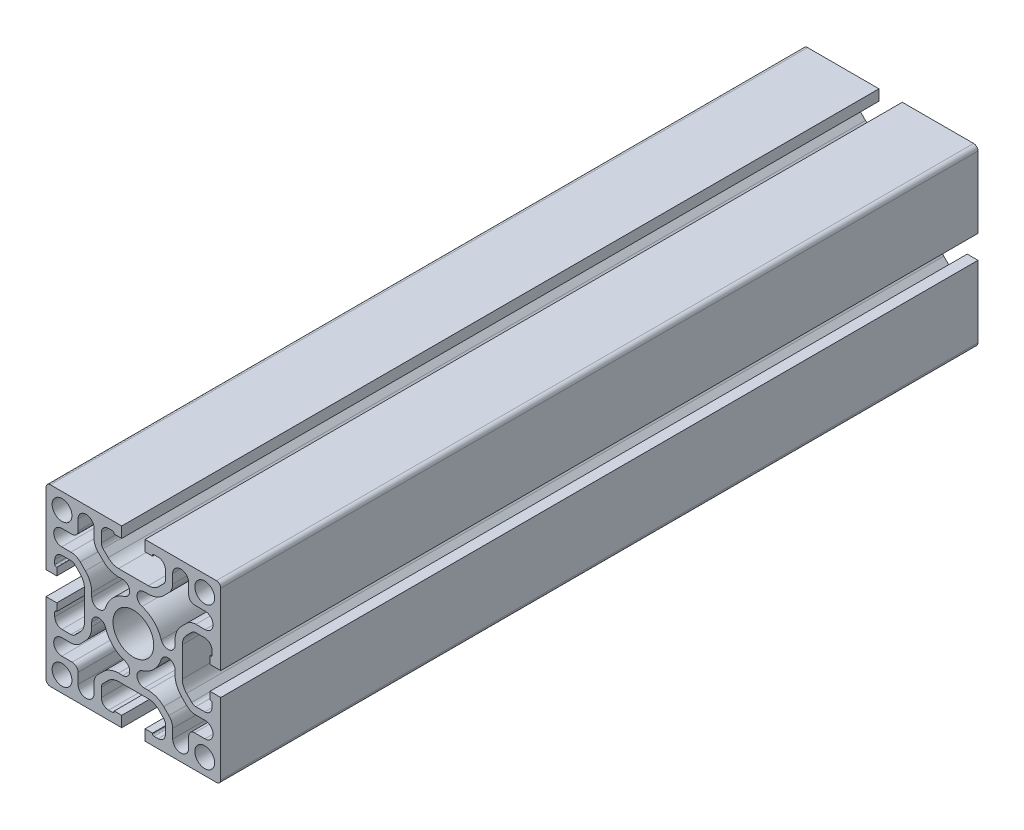
SolidWorks part; units mm, degrees
ref_plane "Płaszczyzna przednia" through (0, 0, 0) normal (0, 0, 1) x (1, 0, 0)
ref_plane "Płaszczyzna górna" through (0, 0, 0) normal (0, 1, 0) x (1, 0, 0)
ref_plane "Płaszczyzna prawa" through (0, 0, 0) normal (1, 0, 0) x (0, 0, -1)
ref_plane "Plane1" through (0, 0, 0) normal (0, 0, -1) x (-1, 0, 0)
sketch "Sketch1" plane through (0, 0, 0) normal (0, 0, -1) x (-1, 0, 0)
  line L0 (5.1034, -14.3) -> (3.6784, -14.3)
  line L1 (14.3, -3.6784) -> (14.3, -5.1134)
  line L2 (16.4818, -10.4017) -> (18.2431, -12.173)
  line L3 (21.434, -13.5) -> (24.6, -13.5)
  line L4 (24.6, -19) -> (21, -19)
  line L5 (19, -21) -> (19, -24.6)
  line L6 (13.5, -24.6) -> (13.5, -21.454)
  line L7 (12.182, -18.272) -> (10.4067, -16.4967)
  line L8 (-3.6784, -14.3) -> (-5.1034, -14.3)
  line L9 (-10.4067, -16.4967) -> (-12.182, -18.272)
  line L10 (-13.5, -21.454) -> (-13.5, -24.6)
  line L11 (-19, -24.6) -> (-19, -21)
  line L12 (-21, -19) -> (-24.6, -19)
  line L13 (-24.6, -13.5) -> (-21.434, -13.5)
  line L14 (-18.2431, -12.173) -> (-16.4818, -10.4017)
  line L15 (-14.3, -5.1134) -> (-14.3, -3.6784)
  line L16 (-5.1034, 14.3) -> (-3.6784, 14.3)
  line L17 (-14.3, 3.6784) -> (-14.3, 5.1134)
  line L18 (-16.4818, 10.4017) -> (-18.2431, 12.173)
  line L19 (-21.434, 13.5) -> (-24.6, 13.5)
  line L20 (-24.6, 19) -> (-21, 19)
  line L21 (-19, 21) -> (-19, 24.6)
  line L22 (-13.5, 24.6) -> (-13.5, 21.454)
  line L23 (-12.182, 18.272) -> (-10.4067, 16.4967)
  line L24 (3.6784, 14.3) -> (5.1034, 14.3)
  line L25 (10.4067, 16.4967) -> (12.182, 18.272)
  line L26 (13.5, 21.454) -> (13.5, 24.6)
  line L27 (19, 24.6) -> (19, 21)
  line L28 (21, 19) -> (24.6, 19)
  line L29 (24.6, 13.5) -> (21.434, 13.5)
  line L30 (18.2431, 12.173) -> (16.4818, 10.4017)
  line L31 (14.3, 5.1134) -> (14.3, 3.6784)
  line L32 (5.1, 16.8) -> (-5.11, 16.8)
  line L33 (-8.6455, 18.2645) -> (-10.42, 20.04)
  line L34 (-11, 21.45) -> (-11, 24.5)
  line L35 (-8.5, 27) -> (-7.07, 27)
  line L36 (-6.57, 26.5) -> (-6.57, 26.3)
  line L37 (-6.57, 26.3) -> (-4, 26.3)
  line L38 (-4, 26.3) -> (-4, 30)
  line L39 (-4, 30) -> (-28.5, 30)
  line L40 (-30, 28.5) -> (-30, 4)
  line L41 (-30, 4) -> (-26.3, 4)
  line L42 (-26.3, 4) -> (-26.3, 6.57)
  line L43 (-26.3, 6.57) -> (-26.5, 6.57)
  line L44 (-27, 7.07) -> (-27, 8.5)
  line L45 (-24.5, 11) -> (-21.45, 11)
  line L46 (-20.0358, 10.4142) -> (-18.27, 8.65)
  line L47 (-16.8, 5.11) -> (-16.8, -5.1)
  line L48 (-18.2645, -8.6355) -> (-20.04, -10.41)
  line L49 (-21.45, -11) -> (-24.5, -11)
  line L50 (-27, -8.5) -> (-27, -7.07)
  line L51 (-26.5, -6.57) -> (-26.3, -6.57)
  line L52 (-26.3, -6.57) -> (-26.3, -4)
  line L53 (-26.3, -4) -> (-30, -4)
  line L54 (-30, -4) -> (-30, -28.5)
  line L55 (-28.5, -30) -> (-4, -30)
  line L56 (-4, -30) -> (-4, -26.3)
  line L57 (-4, -26.3) -> (-6.57, -26.3)
  line L58 (-6.57, -26.3) -> (-6.57, -26.5)
  line L59 (-7.07, -27) -> (-8.5, -27)
  line L60 (-11, -24.5) -> (-11, -21.45)
  line L61 (-10.4142, -20.0358) -> (-8.65, -18.26)
  line L62 (-5.11, -16.8) -> (5.1, -16.8)
  line L63 (8.64, -18.26) -> (10.41, -20.03)
  line L64 (11, -21.45) -> (11, -24.5)
  line L65 (8.5, -27) -> (7.07, -27)
  line L66 (6.57, -26.5) -> (6.57, -26.3)
  line L67 (6.57, -26.3) -> (4, -26.3)
  line L68 (4, -26.3) -> (4, -30)
  line L69 (4, -30) -> (28.5, -30)
  line L70 (30, -28.5) -> (30, -4)
  line L71 (30, -4) -> (26.3, -4)
  line L72 (26.3, -4) -> (26.3, -6.57)
  line L73 (26.3, -6.57) -> (26.5, -6.57)
  line L74 (27, -7.07) -> (27, -8.5)
  line L75 (24.5, -11) -> (21.45, -11)
  line L76 (20.0358, -10.4142) -> (18.26, -8.64)
  line L77 (16.8, -5.1) -> (16.8, 5.11)
  line L78 (18.26, 8.65) -> (20.0358, 10.4142)
  line L79 (21.45, 11) -> (24.5, 11)
  line L80 (27, 8.5) -> (27, 7.07)
  line L81 (26.5, 6.57) -> (26.3, 6.57)
  line L82 (26.3, 6.57) -> (26.3, 4)
  line L83 (26.3, 4) -> (30, 4)
  line L84 (30, 4) -> (30, 28.5)
  line L85 (28.5, 30) -> (4, 30)
  line L86 (4, 30) -> (4, 26.3)
  line L87 (4, 26.3) -> (6.57, 26.3)
  line L88 (6.57, 26.3) -> (6.57, 26.5)
  line L89 (7.07, 27) -> (8.5, 27)
  line L90 (11, 24.5) -> (11, 21.45)
  line L91 (10.4142, 20.0358) -> (8.64, 18.27)
  circle A0 centre (-24.5, 24.5) radius 3.4
  circle A1 centre (24.5, 24.5) radius 3.4
  circle A2 centre (-24.5, -24.49) radius 3.4
  circle A3 centre (24.5, -24.49) radius 3.4
  circle A4 centre (0, 0) radius 7
  arc A5 (3.6784, -14.3) -> (2.9597, -9.552) centre (3.6784, -11.8716) cw
  arc A6 (2.9597, -9.552) -> (9.552, -2.9597) centre (0, 0) ccw
  arc A7 (9.552, -2.9597) -> (14.3, -3.6784) centre (11.8716, -3.6784) cw
  arc A8 (14.3, -5.1134) -> (16.4818, -10.4017) centre (21.8, -5.1134) ccw
  arc A9 (18.2431, -12.173) -> (21.434, -13.5) centre (21.434, -9) ccw
  arc A10 (24.6, -13.5) -> (24.6, -19) centre (24.6, -16.25) cw
  arc A11 (21, -19) -> (19, -21) centre (21, -21) ccw
  arc A12 (19, -24.6) -> (13.5, -24.6) centre (16.25, -24.6) cw
  arc A13 (13.5, -21.454) -> (12.182, -18.272) centre (9, -21.454) ccw
  arc A14 (10.4067, -16.4967) -> (5.1034, -14.3) centre (5.1034, -21.8) ccw
  arc A15 (-9.552, -2.9597) -> (-2.9597, -9.552) centre (0, 0) ccw
  arc A16 (-2.9597, -9.552) -> (-3.6784, -14.3) centre (-3.6784, -11.8716) cw
  arc A17 (-5.1034, -14.3) -> (-10.4067, -16.4967) centre (-5.1034, -21.8) ccw
  arc A18 (-12.182, -18.272) -> (-13.5, -21.454) centre (-9, -21.454) ccw
  arc A19 (-13.5, -24.6) -> (-19, -24.6) centre (-16.25, -24.6) cw
  arc A20 (-19, -21) -> (-21, -19) centre (-21, -21) ccw
  arc A21 (-24.6, -19) -> (-24.6, -13.5) centre (-24.6, -16.25) cw
  arc A22 (-21.434, -13.5) -> (-18.2431, -12.173) centre (-21.434, -9) ccw
  arc A23 (-16.4818, -10.4017) -> (-14.3, -5.1134) centre (-21.8, -5.1134) ccw
  arc A24 (-14.3, -3.6784) -> (-9.552, -2.9597) centre (-11.8716, -3.6784) cw
  arc A25 (-3.6784, 14.3) -> (-2.9597, 9.552) centre (-3.6784, 11.8716) cw
  arc A26 (-2.9597, 9.552) -> (-9.552, 2.9597) centre (0, 0) ccw
  arc A27 (-9.552, 2.9597) -> (-14.3, 3.6784) centre (-11.8716, 3.6784) cw
  arc A28 (-14.3, 5.1134) -> (-16.4818, 10.4017) centre (-21.8, 5.1134) ccw
  arc A29 (-18.2431, 12.173) -> (-21.434, 13.5) centre (-21.434, 9) ccw
  arc A30 (-24.6, 13.5) -> (-24.6, 19) centre (-24.6, 16.25) cw
  arc A31 (-21, 19) -> (-19, 21) centre (-21, 21) ccw
  arc A32 (-19, 24.6) -> (-13.5, 24.6) centre (-16.25, 24.6) cw
  arc A33 (-13.5, 21.454) -> (-12.182, 18.272) centre (-9, 21.454) ccw
  arc A34 (-10.4067, 16.4967) -> (-5.1034, 14.3) centre (-5.1034, 21.8) ccw
  arc A35 (9.552, 2.9597) -> (2.9597, 9.552) centre (0, 0) ccw
  arc A36 (2.9597, 9.552) -> (3.6784, 14.3) centre (3.6784, 11.8716) cw
  arc A37 (5.1034, 14.3) -> (10.4067, 16.4967) centre (5.1034, 21.8) ccw
  arc A38 (12.182, 18.272) -> (13.5, 21.454) centre (9, 21.454) ccw
  arc A39 (13.5, 24.6) -> (19, 24.6) centre (16.25, 24.6) cw
  arc A40 (19, 21) -> (21, 19) centre (21, 21) ccw
  arc A41 (24.6, 19) -> (24.6, 13.5) centre (24.6, 16.25) cw
  arc A42 (21.434, 13.5) -> (18.2431, 12.173) centre (21.434, 9) ccw
  arc A43 (16.4818, 10.4017) -> (14.3, 5.1134) centre (21.8, 5.1134) ccw
  arc A44 (14.3, 3.6784) -> (9.552, 2.9597) centre (11.8716, 3.6784) cw
  arc A45 (-5.11, 16.8) -> (-8.6455, 18.2645) centre (-5.11, 21.8) cw
  arc A46 (-10.42, 20.04) -> (-11, 21.45) centre (-8.9925, 21.4515) cw
  arc A47 (-11, 24.5) -> (-8.5, 27) centre (-8.5, 24.5) cw
  arc A48 (-7.07, 27) -> (-6.57, 26.5) centre (-7.07, 26.5) cw
  arc A49 (-28.5, 30) -> (-30, 28.5) centre (-28.5, 28.5) ccw
  arc A50 (-26.5, 6.57) -> (-27, 7.07) centre (-26.5, 7.07) cw
  arc A51 (-27, 8.5) -> (-24.5, 11) centre (-24.5, 8.5) cw
  arc A52 (-21.45, 11) -> (-20.0358, 10.4142) centre (-21.45, 9) cw
  arc A53 (-18.27, 8.65) -> (-16.8, 5.11) centre (-21.7951, 5.111) cw
  arc A54 (-16.8, -5.1) -> (-18.2645, -8.6355) centre (-21.8, -5.1) cw
  arc A55 (-20.04, -10.41) -> (-21.45, -11) centre (-21.4424, -9.0384) cw
  arc A56 (-24.5, -11) -> (-27, -8.5) centre (-24.5, -8.5) cw
  arc A57 (-27, -7.07) -> (-26.5, -6.57) centre (-26.5, -7.07) cw
  arc A58 (-30, -28.5) -> (-28.5, -30) centre (-28.5, -28.5) ccw
  arc A59 (-6.57, -26.5) -> (-7.07, -27) centre (-7.07, -26.5) cw
  arc A60 (-8.5, -27) -> (-11, -24.5) centre (-8.5, -24.5) cw
  arc A61 (-11, -21.45) -> (-10.4142, -20.0358) centre (-9, -21.45) cw
  arc A62 (-8.65, -18.26) -> (-5.11, -16.8) centre (-5.1017, -21.8418) cw
  arc A63 (5.1, -16.8) -> (8.64, -18.26) centre (5.0917, -21.8418) cw
  arc A64 (10.41, -20.03) -> (11, -21.45) centre (8.9927, -21.4515) cw
  arc A65 (11, -24.5) -> (8.5, -27) centre (8.5, -24.5) cw
  arc A66 (7.07, -27) -> (6.57, -26.5) centre (7.07, -26.5) cw
  arc A67 (28.5, -30) -> (30, -28.5) centre (28.5, -28.5) ccw
  arc A68 (26.5, -6.57) -> (27, -7.07) centre (26.5, -7.07) cw
  arc A69 (27, -8.5) -> (24.5, -11) centre (24.5, -8.5) cw
  arc A70 (21.45, -11) -> (20.0358, -10.4142) centre (21.45, -9) cw
  arc A71 (18.26, -8.64) -> (16.8, -5.1) centre (21.8418, -5.0917) cw
  arc A72 (16.8, 5.11) -> (18.26, 8.65) centre (21.8418, 5.1017) cw
  arc A73 (20.0358, 10.4142) -> (21.45, 11) centre (21.45, 9) cw
  arc A74 (24.5, 11) -> (27, 8.5) centre (24.5, 8.5) cw
  arc A75 (27, 7.07) -> (26.5, 6.57) centre (26.5, 7.07) cw
  arc A76 (30, 28.5) -> (28.5, 30) centre (28.5, 28.5) ccw
  arc A77 (6.57, 26.5) -> (7.07, 27) centre (7.0699, 26.5001) cw
  arc A78 (8.5, 27) -> (11, 24.5) centre (8.5, 24.5) cw
  arc A79 (11, 21.45) -> (10.4142, 20.0358) centre (9, 21.45) cw
  arc A80 (8.64, 18.27) -> (5.1, 16.8) centre (5.101, 21.7951) cw
extrude "Boss-Extrude1" add sketch "Sketch1" against normal blind 260
